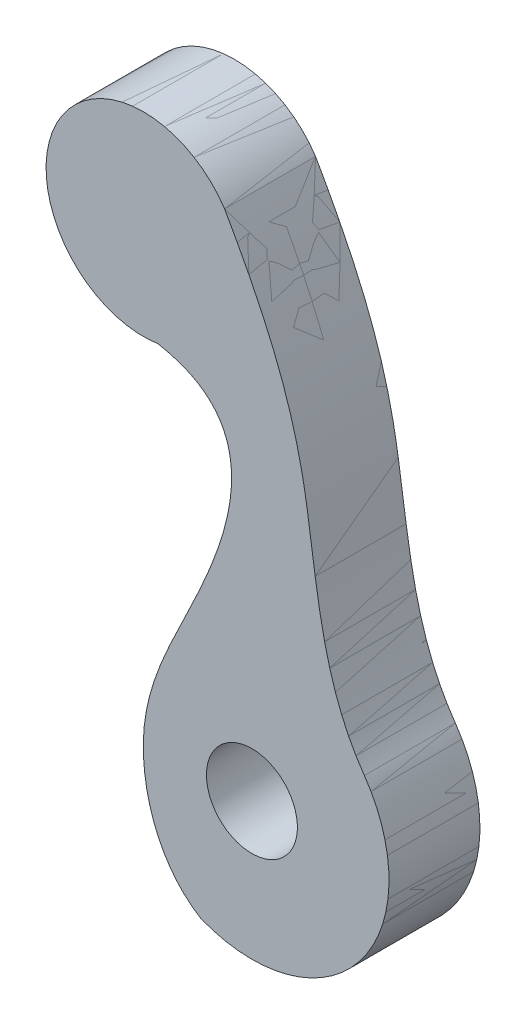
SolidWorks part; units mm, degrees
ref_plane "Alzado" through (0, 0, 0) normal (0, 0, 1) x (1, 0, 0)
ref_plane "Planta" through (0, 0, 0) normal (0, 1, 0) x (1, 0, 0)
ref_plane "Vista lateral" through (0, 0, 0) normal (1, 0, 0) x (0, 0, -1)
ref_plane "Plano1" through (0, 0, 5) normal (0, 0, 1) x (1, 0, 0)
sketch "Croquis1" plane through (0, 0, 5) normal (0, 0, 1) x (1, 0, 0)
  circle A0 centre (0, 0) radius 2.5
  arc A1 (-1.5024, 27.4463) -> (-5.1652, 19.193) centre (-5.9637, 24.4868) ccw
  arc A2 (-2.7914, -7.001) -> (6.184, 4.3085) centre (0, 0) ccw
  spline S0 degree 3 poles (6.184, 4.3085) (3.6139, 7.9295) (3.5957, 16.9163) (0.7556, 23.4721) (-1.5024, 27.4463) knots 0 0 0 0 0.531518 1 1 1 1
  spline S1 degree 3 poles (-5.1652, 19.193) (0.562, 18.1612) (-2.0209, 9.0935) (-7.2202, 0.9356) (-5.0987, -5.6295) (-2.7914, -7.001) knots 0 0 0 0 0.419324 0.734084 1 1 1 1
extrude "Saliente-Extruir1" add sketch "Croquis1" against normal blind 5
sketch "Croquis2" plane through (0, 0, 5) normal (0, 0, 1) x (1, 0, 0)
  arc A0 (-2.7914, -7.001) -> (6.184, 4.3085) centre (0, 0) ccw construction
  arc A1 (-1.5024, 27.4463) -> (-5.1652, 19.193) centre (-5.9637, 24.4868) ccw construction
  arc A2 (-2.7914, -7.001) -> (6.184, 4.3085) centre (0, 0) ccw
  arc A3 (-1.5024, 27.4463) -> (-5.1652, 19.193) centre (-5.9637, 24.4868) ccw
  spline S0 degree 3 poles (2708.3473, 1303.9777) (-54.1286, -123.3697) (86.688, 97.2389) (-115.9042, 22.0324) (-963.6113, 2867.0605) knots -4.529879 -4.529879 -4.529879 -4.529879 0.531518 6.501432 6.501432 6.501432 6.501432 only from (6.184, 4.3085) to (-1.5024, 27.4463) construction
  spline S1 degree 3 poles (-2509.42, -1630.7101) (3.4836, 119.8637) (11.3863, 30.1303) (-21.8202, -21.9727) (135.6368, -111.8772) (820.7808, 2873.4638) knots -2.578693 -2.578693 -2.578693 -2.578693 0.419324 0.734084 3.808106 3.808106 3.808106 3.808106 only from (-5.1652, 19.193) to (-2.7914, -7.001) construction
  spline S2 degree 3 poles (6.184, 4.3085) (3.6139, 7.9295) (3.5957, 16.9163) (0.7556, 23.4721) (-1.5024, 27.4463) knots 0 0 0 0 0.531518 1 1 1 1
  spline S3 degree 3 poles (-5.1652, 19.193) (0.562, 18.1612) (-2.0209, 9.0935) (-7.2202, 0.9356) (-5.0987, -5.6295) (-2.7914, -7.001) knots 0 0 0 0 0.419324 0.734084 1 1 1 1
surface "Superficie-Extruir1" sketch "Croquis2" parameters "D1"=5
